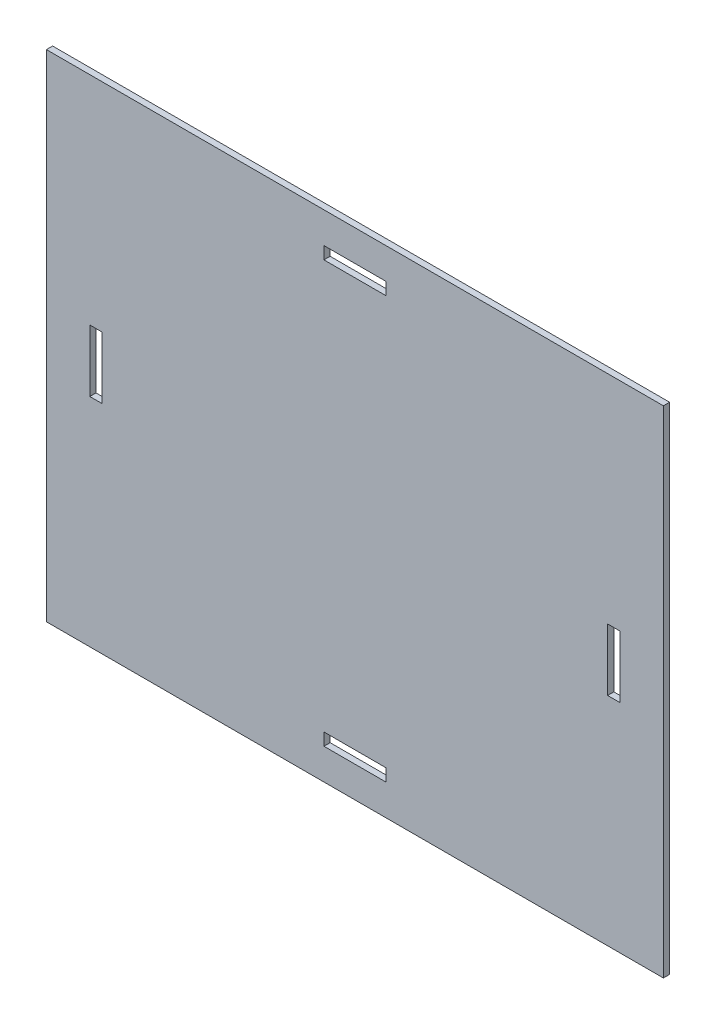
SolidWorks part; units mm, degrees
ref_plane "前视基准面" through (0, 0, 0) normal (0, 0, 1) x (1, 0, 0)
ref_plane "上视基准面" through (0, 0, 0) normal (0, 1, 0) x (1, 0, 0)
ref_plane "右视基准面" through (0, 0, 0) normal (1, 0, 0) x (0, 0, -1)
sketch "草图1" plane through (0, 0, 0) normal (0, 0, 1) x (1, 0, 0)
  line L1 (-92.443, 75.7769) -> (7.157, 75.7769)
  line L2 (-92.443, 75.7769) -> (-92.443, -4.2231)
  line L3 (-92.443, -4.2231) -> (7.157, -4.2231)
  line L4 (7.157, 75.7769) -> (7.157, -4.2231)
  dimension "D1" = 80
  dimension "D2" = 99.6
extrude "凸台-拉伸1" add sketch "草图1" along normal blind 1 contours L1 L4 L3 L2
sketch "草图2" plane through (0, 0, 1) normal (0, 0, 1) x (1, 0, 0)
  line L0 (-92.443, 75.7769) -> (7.157, 75.7769) construction
  line L1 (-47.643, 68.7769) -> (-37.643, 68.7769)
  line L2 (-47.643, 68.7769) -> (-47.643, 70.7769)
  line L3 (-47.643, 70.7769) -> (-37.643, 70.7769)
  line L4 (-37.643, 68.7769) -> (-37.643, 70.7769)
  line L5 (-47.643, 68.7769) -> (-37.643, 70.7769) construction
  line L6 (-47.643, 70.7769) -> (-37.643, 68.7769) construction
  line L7 (-92.443, 35.7769) -> (7.157, 35.7769) construction
  line L8 (-92.443, 75.7769) -> (-92.443, -4.2231) construction
  line L9 (7.157, 75.7769) -> (7.157, -4.2231) construction
  line L10 (-47.643, 0.7769) -> (-37.643, 2.7769) construction
  line L11 (-47.643, 2.7769) -> (-37.643, 0.7769) construction
  line L12 (-37.643, 2.7769) -> (-37.643, 0.7769)
  line L13 (-47.643, 0.7769) -> (-37.643, 0.7769)
  line L14 (-47.643, 2.7769) -> (-47.643, 0.7769)
  line L15 (-47.643, 2.7769) -> (-37.643, 2.7769)
  line L16 (-42.643, 75.7769) -> (-42.643, -4.2231) construction
  line L17 (-85.443, 30.7769) -> (-83.443, 30.7769)
  line L18 (-85.443, 30.7769) -> (-85.443, 40.7769)
  line L19 (-85.443, 40.7769) -> (-83.443, 40.7769)
  line L20 (-83.443, 30.7769) -> (-83.443, 40.7769)
  line L21 (-85.443, 30.7769) -> (-83.443, 40.7769) construction
  line L22 (-85.443, 40.7769) -> (-83.443, 30.7769) construction
  line L23 (-92.443, -4.2231) -> (7.157, -4.2231) construction
  line L24 (0.157, 40.7769) -> (-1.843, 30.7769) construction
  line L25 (0.157, 30.7769) -> (-1.843, 40.7769) construction
  line L26 (-1.843, 30.7769) -> (-1.843, 40.7769)
  line L27 (0.157, 30.7769) -> (0.157, 40.7769)
  line L28 (0.157, 30.7769) -> (-1.843, 30.7769)
  line L29 (0.157, 40.7769) -> (-1.843, 40.7769)
  point P0 (-42.643, 69.7769)
  point P7 (-42.643, 75.7769)
  point P18 (-42.643, 1.7769)
  point P19 (-84.443, 35.7769)
  point P32 (-0.843, 35.7769)
  dimension "D1" = 10
  dimension "D2" = 2
  dimension "D3" = 5
  dimension "D4" = 2
  dimension "D5" = 10
  dimension "D6" = 8
extrude "切除-拉伸1" cut sketch "草图2" against normal blind 10
